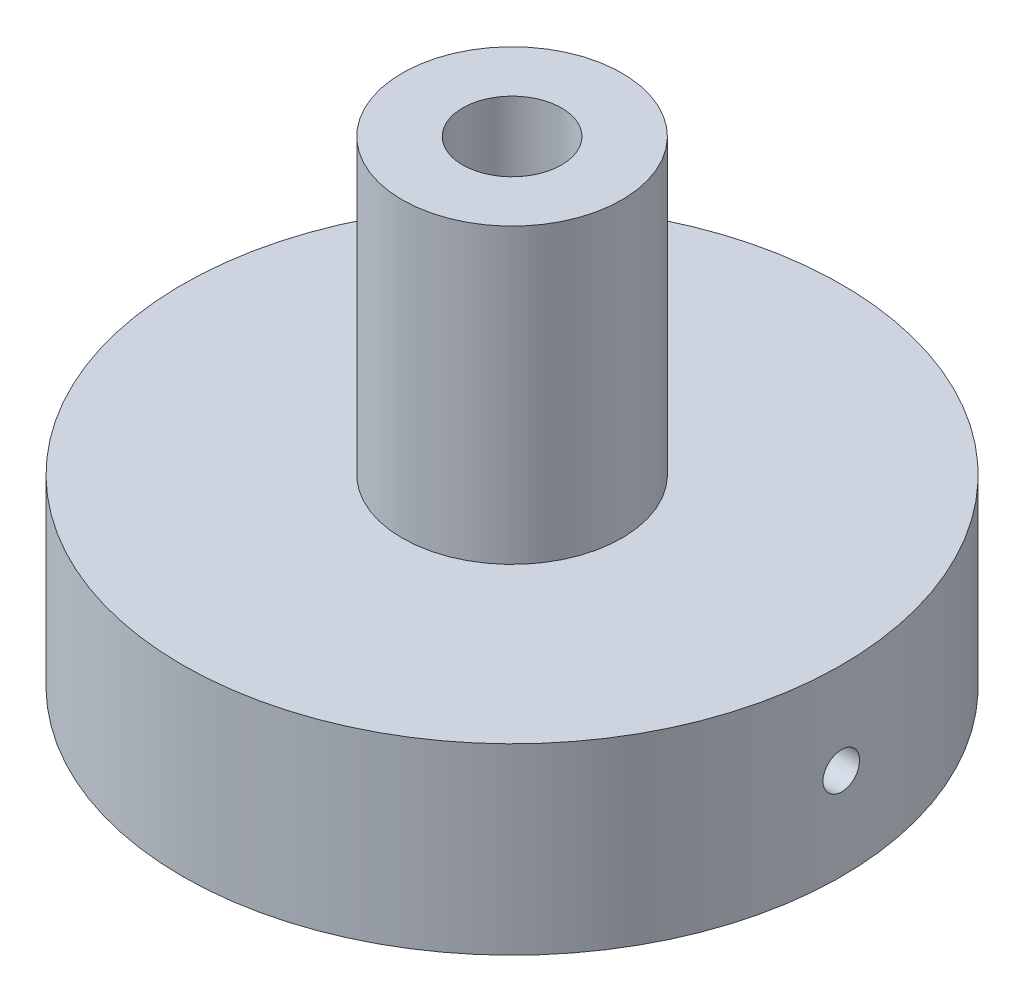
SolidWorks part; units mm, degrees
ref_plane "Front Plane" through (0, 0, 0) normal (0, 0, 1) x (1, 0, 0)
ref_plane "Top Plane" through (0, 0, 0) normal (0, 1, 0) x (1, 0, 0)
ref_plane "Right Plane" through (0, 0, 0) normal (1, 0, 0) x (0, 0, -1)
sketch "Sketch1" plane through (0, 0, 0) normal (0, 1, 0) x (1, 0, 0)
  circle A0 centre (0, 0) radius 4.5
  dimension "D1" = 9
extrude "Boss-Extrude1" add sketch "Sketch1" along normal blind 2.5
sketch "Sketch2" plane through (0, 2.5, 0) normal (0, 1, 0) x (1, 0, 0)
  circle A0 centre (0, 0) radius 1.5
  circle A1 centre (0, 0) radius 0.675
  dimension "D1" = 1.35
  dimension "D2" = 3
extrude "Boss-Extrude2" add sketch "Sketch2" along normal blind 4
sketch "Sketch3" plane through (0, 0, 0) normal (0, 0, 1) x (1, 0, 0)
  line L0 (0, 0) -> (0, 2.5) construction
  line L1 (4.5, 2.5) -> (-4.5, 2.5) construction
  line L2 (0, 1.25) -> (4.5, 1.25) construction
  line L3 (4.5, 0) -> (4.5, 2.5) construction
  line L4 (4.5, 1.25) -> (4.5, 1.5)
  line L5 (4.5, 1.5) -> (0, 1.5)
  line L6 (0, 1.5) -> (0, 1.25)
  line L7 (0, 1.25) -> (4.5, 1.25)
  dimension "D1" = 0.25
revolve "Cut-Revolve1" cut sketch "Sketch3" angle 360 about L7
sketch "Sketch5" plane through (0, 2.5, 0) normal (0, 1, 0) x (1, 0, 0)
  circle A0 centre (0, 0) radius 0.4065
  circle A1 centre (0, 0) radius 0.675 construction
extrude "Cut-Extrude2" cut sketch "Sketch5" against normal blind 2
